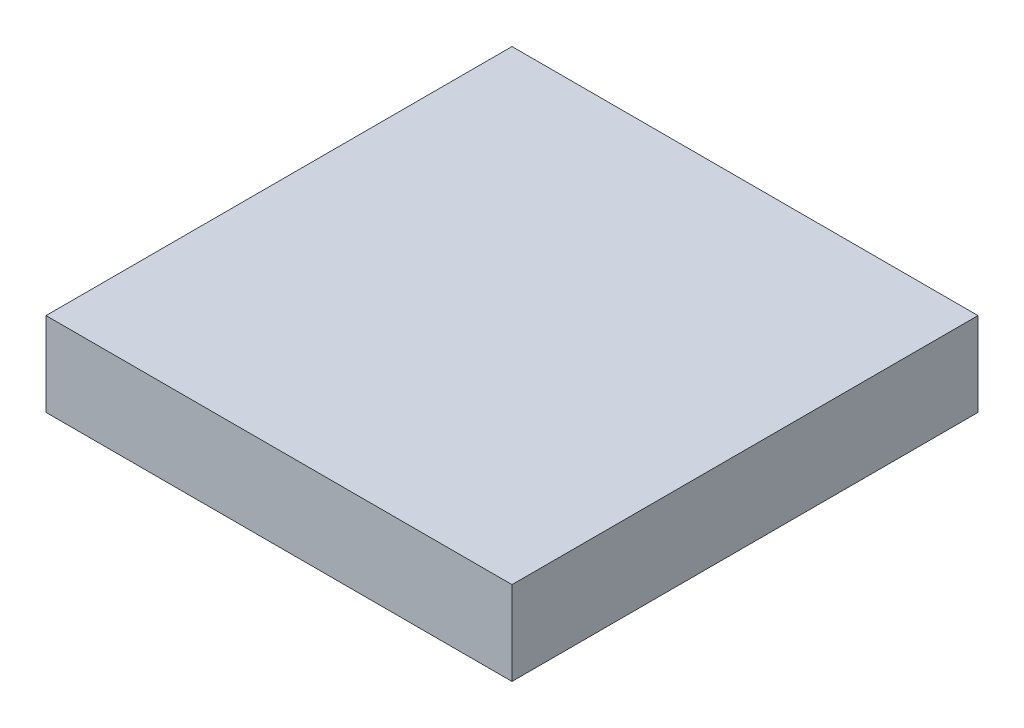
SolidWorks part; units mm, degrees
material "Perspex (TM) GS Acrylic Cast Sheet"
ref_plane "Front Plane" through (0, 0, 0) normal (0, 0, 1) x (1, 0, 0)
ref_plane "Top Plane" through (0, 0, 0) normal (0, 1, 0) x (1, 0, 0)
ref_plane "Right Plane" through (0, 0, 0) normal (1, 0, 0) x (0, 0, -1)
sketch "Sketch1" plane through (0, 0, 0) normal (0, 1, 0) x (1, 0, 0)
  line L1 (-12.5, -12.5) -> (12.5, -12.5)
  line L2 (-12.5, -12.5) -> (-12.5, 12.5)
  line L3 (-12.5, 12.5) -> (12.5, 12.5)
  line L4 (12.5, -12.5) -> (12.5, 12.5)
  line L5 (-12.5, -12.5) -> (12.5, 12.5) construction
  line L6 (-12.5, 12.5) -> (12.5, -12.5) construction
  point P0 (0, 0)
  point P5 (0, 0)
  dimension "D1" = 25
  dimension "D2" = 25
extrude "Boss-Extrude1" add sketch "Sketch1" along normal blind 4.5
sketch "Sketch3" plane through (0, 0, 0) normal (0, -1, 0) x (1, 0, 0)
  circle A0 centre (0, 0) radius 3.125
  dimension "D1" = 6.25
sketch "Sketch4" plane through (0, 4.5, 0) normal (0, 1, 0) x (1, 0, 0)
  circle A0 centre (0, 0) radius 3.125
